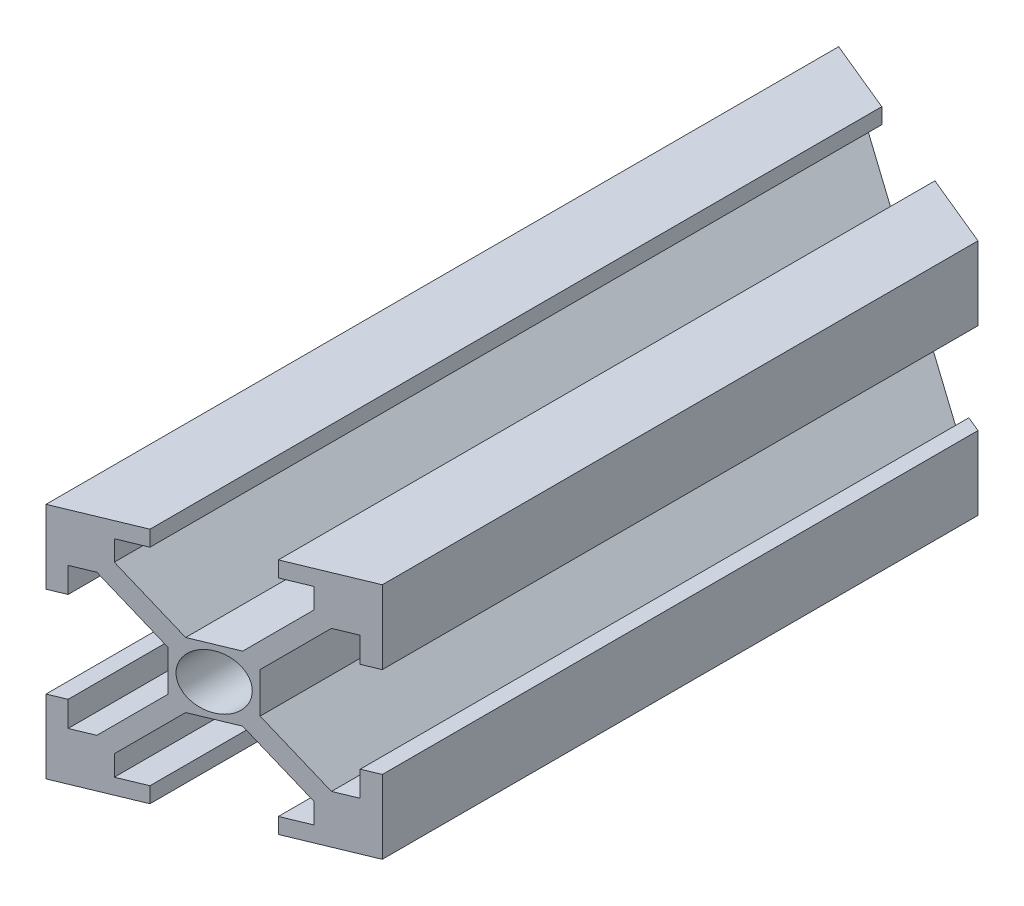
SolidWorks part; units mm, degrees
ref_plane "Front Plane" through (0, 0, 0) normal (0, 0, 1) x (1, 0, 0)
ref_plane "Top Plane" through (0, 0, 0) normal (0, 1, 0) x (1, 0, 0)
ref_plane "Right Plane" through (0, 0, 0) normal (1, 0, 0) x (0, 0, -1)
sketch "Sketch3" plane through (0, 0, 0) normal (0, 0, 1) x (1, 0, 0)
  line L0 (0, 0) -> (0.7778, -0.7778)
  line L5 (-4.1, 4.1) -> (4.1, -4.1) construction
  line L6 (-4.1, -4.1) -> (4.1, 4.1) construction
  line L7 (0, 0) -> (-0.7778, 0.7778)
  line L8 (-0.7778, 0.7778) -> (-4.1, -2.5444) construction
  line L9 (0.7778, -0.7778) -> (-2.5444, -4.1) construction
  line L10 (-4.1, -2.5444) -> (-10.464, -8.9083)
  line L11 (-15, -15) -> (15, -15)
  line L12 (-15, -15) -> (-15, 15)
  line L13 (-15, 15) -> (15, 15)
  line L14 (15, -15) -> (15, 15)
  line L15 (-15, -15) -> (15, 15) construction
  line L16 (-15, 15) -> (15, -15) construction
  line L17 (-15, 0) -> (15, 0) construction
  line L18 (0, -15) -> (0, 15) construction
  line L19 (-2.5444, -4.1) -> (-8.9083, -10.464)
  line L20 (-8.9083, -10.464) -> (-8.9083, -13.0281)
  line L21 (-8.9083, -13.0281) -> (-5.7263, -13.0281)
  line L22 (-5.7263, -13.0281) -> (-5.7263, -15)
  line L23 (-13.0281, -5.7263) -> (-15, -5.7263)
  line L24 (-13.0281, -8.9083) -> (-13.0281, -5.7263)
  line L25 (-10.464, -8.9083) -> (-13.0281, -8.9083)
  line L26 (-5.7263, 13.0281) -> (-5.7263, 15)
  line L27 (-8.9083, 13.0281) -> (-5.7263, 13.0281)
  line L28 (-8.9083, 10.464) -> (-8.9083, 13.0281)
  line L29 (-2.5444, 4.1) -> (-8.9083, 10.464)
  line L30 (-4.1, 2.5444) -> (-10.464, 8.9083)
  line L31 (-10.464, 8.9083) -> (-13.0281, 8.9083)
  line L32 (-13.0281, 8.9083) -> (-13.0281, 5.7263)
  line L33 (-13.0281, 5.7263) -> (-15, 5.7263)
  line L34 (5.7263, 13.0281) -> (5.7263, 15)
  line L35 (8.9083, 13.0281) -> (5.7263, 13.0281)
  line L36 (8.9083, 10.464) -> (8.9083, 13.0281)
  line L37 (2.5444, 4.1) -> (8.9083, 10.464)
  line L38 (4.1, 2.5444) -> (10.464, 8.9083)
  line L39 (10.464, 8.9083) -> (13.0281, 8.9083)
  line L40 (13.0281, 8.9083) -> (13.0281, 5.7263)
  line L41 (13.0281, 5.7263) -> (15, 5.7263)
  line L42 (5.7263, -13.0281) -> (5.7263, -15)
  line L43 (8.9083, -13.0281) -> (5.7263, -13.0281)
  line L44 (8.9083, -10.464) -> (8.9083, -13.0281)
  line L45 (2.5444, -4.1) -> (8.9083, -10.464)
  line L46 (13.0281, -5.7263) -> (15, -5.7263)
  line L47 (13.0281, -8.9083) -> (13.0281, -5.7263)
  line L48 (10.464, -8.9083) -> (13.0281, -8.9083)
  line L49 (4.1, -2.5444) -> (10.464, -8.9083)
  line L50 (-2.5444, -4.1) -> (2.5444, -4.1)
  line L51 (4.1, -2.5444) -> (4.1, 2.5444)
  line L52 (2.5444, 4.1) -> (-2.5444, 4.1)
  line L53 (-4.1, 2.5444) -> (-4.1, -2.5444)
  circle A0 centre (0, 0) radius 3.4
  dimension "D1" = 6.8
  dimension "D4" = 1.1
  dimension "D5" = 1.1
  dimension "D6" = 2.2
  dimension "D7" = 30
  dimension "D8" = 30
  dimension "D9" = 9
extrude "Boss-Extrude1" add sketch "Sketch3" along normal blind 100 contours L30 L53 L10 L25 L24 L23 L12 L11 L22 L21 L20 L19 L50 L45 L44 L43 L42 L14 L46 L47 L48 L49 L51 L38 L39 L40 L41 L13 L34 L35 L36 L37 L52 L29 L28 L27 L26 L33 L32 L31 A0
sketch "Sketch4" plane through (0, 15, 0) normal (0, 1, 0) x (1, 0, 0)
  line L0 (-15, -100) -> (15, -100)
  line L1 (-15, -100) -> (15, -87.5736)
  line L2 (15, -100) -> (15, 0) construction
  line L3 (15, -87.5736) -> (15, -100)
  dimension "D1" = 157.5
extrude "Cut-Extrude1" cut sketch "Sketch4" against normal blind 38
sketch "Sketch5" plane through (0, 15, 0) normal (0, 1, 0) x (1, 0, 0)
  line L0 (-15, 0) -> (15, 0)
  line L1 (-15, 0) -> (15, -12.4264)
  line L2 (15, -87.5736) -> (15, 0) construction
  line L3 (15, 0) -> (15, -12.4264)
  dimension "D1" = 22.5
extrude "Cut-Extrude2" cut sketch "Sketch5" against normal blind 38 contours L3 L1 L0
